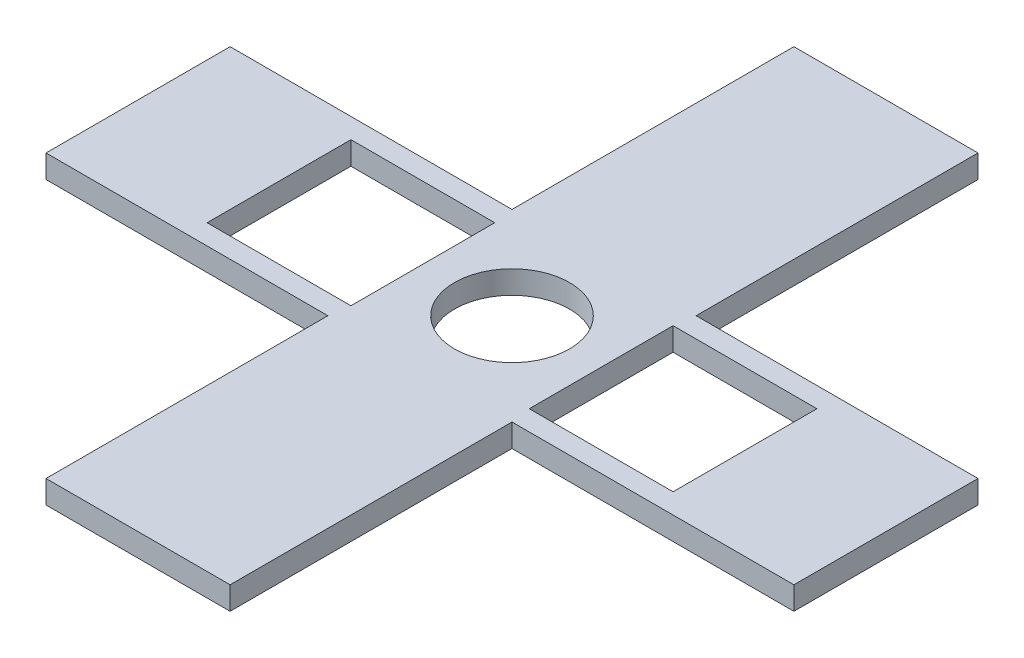
SolidWorks part; units mm, degrees
ref_plane "Front Plane" through (0, 0, 0) normal (0, 0, 1) x (1, 0, 0)
ref_plane "Top Plane" through (0, 0, 0) normal (0, 1, 0) x (1, 0, 0)
ref_plane "Right Plane" through (0, 0, 0) normal (1, 0, 0) x (0, 0, -1)
sketch "Sketch1" plane through (0, 0, 0) normal (0, 1, 0) x (1, 0, 0)
  line L1 (-20.6375, 5.08) -> (-5.08, 5.08)
  line L2 (-20.6375, 5.08) -> (-20.6375, -5.08)
  line L3 (5.08, -5.08) -> (20.6375, -5.08)
  line L4 (20.6375, 5.08) -> (20.6375, -5.08)
  line L5 (-20.6375, 5.08) -> (20.6375, -5.08) construction
  line L6 (-20.6375, -5.08) -> (20.6375, 5.08) construction
  line L7 (-5.08, 20.6375) -> (5.08, 20.6375)
  line L8 (-5.08, 20.6375) -> (-5.08, 5.08)
  line L9 (-5.08, -20.6375) -> (5.08, -20.6375)
  line L10 (5.08, 20.6375) -> (5.08, 5.08)
  line L11 (-5.08, 20.6375) -> (5.08, -20.6375) construction
  line L12 (-5.08, -20.6375) -> (5.08, 20.6375) construction
  line L13 (4.9212, 3.9688) -> (12.8588, 3.9688)
  line L14 (5.08, -5.08) -> (5.08, -20.6375)
  line L15 (-12.8587, 3.9688) -> (-4.9212, 3.9688)
  line L16 (-12.8587, 3.9688) -> (-12.8587, -3.9688)
  line L17 (-12.8587, -3.9688) -> (-4.9212, -3.9688)
  line L18 (-4.9212, 3.9688) -> (-4.9212, -3.9688)
  line L19 (-12.8587, 3.9688) -> (-4.9212, -3.9688) construction
  line L20 (-12.8587, -3.9688) -> (-4.9212, 3.9688) construction
  line L21 (4.9212, 3.9688) -> (4.9212, -3.9687)
  line L22 (4.9212, -3.9687) -> (12.8588, -3.9687)
  line L23 (12.8588, 3.9688) -> (12.8588, -3.9687)
  line L24 (4.9212, 3.9688) -> (12.8588, -3.9687) construction
  line L27 (5.08, 5.08) -> (20.6375, 5.08)
  line L28 (-20.6375, -5.08) -> (-5.08, -5.08)
  line L29 (-5.08, -5.08) -> (-5.08, -20.6375)
  line L30 (4.9212, -3.9687) -> (12.8588, 3.9688) construction
  circle A0 centre (0, 0) radius 3.175
  point P0 (0, 0)
  point P12 (-8.89, 0)
  point P14 (8.89, 0)
  point P19 (-11.1016, 0)
  point P20 (-8.6622, 0)
extrude "Boss-Extrude1" add sketch "Sketch1" along normal blind 1.27
